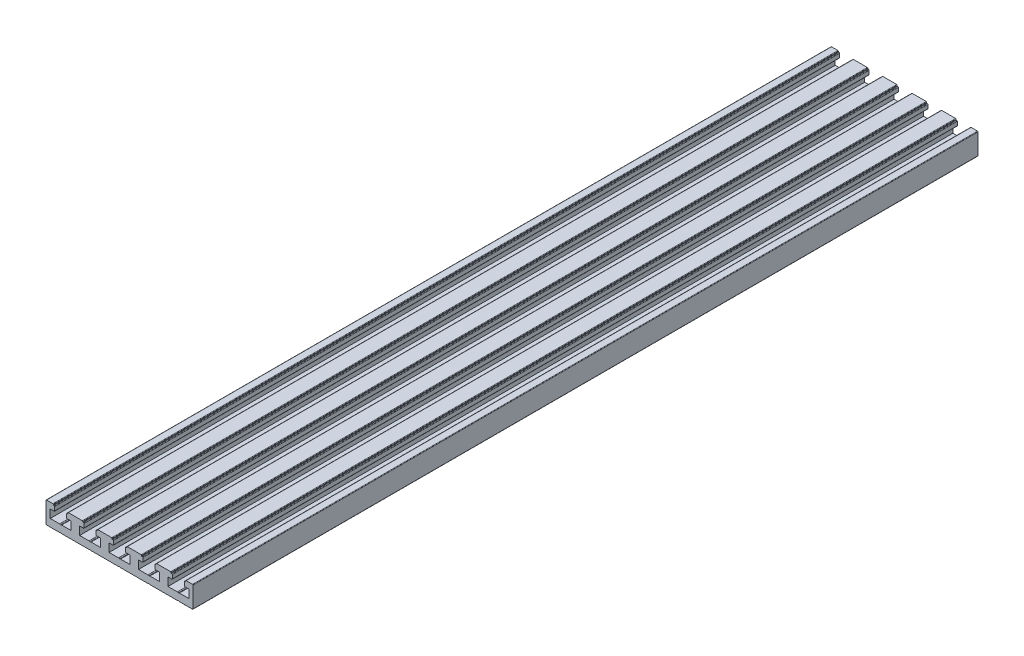
SolidWorks part; units mm, degrees
material "6061-T6 (SS)"
ref_plane "Front Plane" through (0, 0, 0) normal (0, 0, 1) x (1, 0, 0)
ref_plane "Top Plane" through (0, 0, 0) normal (0, 1, 0) x (1, 0, 0)
ref_plane "Right Plane" through (0, 0, 0) normal (1, 0, 0) x (0, 0, -1)
sketch "Sketch1" plane through (0, 0, 0) normal (0, 0, -1) x (-1, 0, 0)
  line L0 (0, 1.72) -> (0, -1.72) construction
  line L1 (-37.45, 8.85) -> (-37.45, -1.65)
  line L2 (-37.2, -1.9) -> (-30.5436, -1.9)
  line L3 (-30.4589, -1.8852) -> (-30, -1.72)
  line L4 (-30, -1.72) -> (-29.5411, -1.8852)
  line L5 (-29.4564, -1.9) -> (-15.5436, -1.9)
  line L6 (-15.4589, -1.8852) -> (-15, -1.72)
  line L7 (-15, -1.72) -> (-14.5411, -1.8852)
  line L8 (-14.4564, -1.9) -> (-0.5436, -1.9)
  line L9 (-0.4589, -1.8852) -> (0, -1.72)
  line L10 (0, -1.72) -> (0.4589, -1.8852)
  line L11 (0.5436, -1.9) -> (14.4564, -1.9)
  line L12 (14.5411, -1.8852) -> (15, -1.72)
  line L13 (15, -1.72) -> (15.4589, -1.8852)
  line L14 (15.5436, -1.9) -> (29.4564, -1.9)
  line L15 (29.5411, -1.8852) -> (30, -1.72)
  line L16 (30, -1.72) -> (30.4589, -1.8852)
  line L17 (30.5436, -1.9) -> (37.2, -1.9)
  line L18 (37.45, -1.65) -> (37.45, 8.85)
  line L19 (37.2, 9.1) -> (33.95, 9.1)
  line L20 (33.7, 8.85) -> (33.7, 8.5)
  line L21 (33.7, 8.5) -> (33.32, 8.5)
  line L22 (33.07, 8.25) -> (33.07, 6.35)
  line L23 (33.32, 6.1) -> (35.3, 6.1)
  line L24 (35.3, 6.1) -> (35.3, 1.9)
  line L25 (35.3, 1.9) -> (30.5436, 1.9)
  line L26 (30.4589, 1.8852) -> (30, 1.72)
  line L27 (30, 1.72) -> (29.5411, 1.8852)
  line L28 (29.4564, 1.9) -> (24.7, 1.9)
  line L29 (24.7, 1.9) -> (24.7, 6.1)
  line L30 (24.7, 6.1) -> (26.68, 6.1)
  line L31 (26.93, 6.35) -> (26.93, 8.25)
  line L32 (26.68, 8.5) -> (26.3, 8.5)
  line L33 (26.3, 8.5) -> (26.3, 8.85)
  line L34 (26.05, 9.1) -> (18.95, 9.1)
  line L35 (18.7, 8.85) -> (18.7, 8.5)
  line L36 (18.7, 8.5) -> (18.32, 8.5)
  line L37 (18.07, 8.25) -> (18.07, 6.35)
  line L38 (18.32, 6.1) -> (20.3, 6.1)
  line L39 (20.3, 6.1) -> (20.3, 1.9)
  line L40 (20.3, 1.9) -> (15.5436, 1.9)
  line L41 (15.4589, 1.8852) -> (15, 1.72)
  line L42 (15, 1.72) -> (14.5411, 1.8852)
  line L43 (14.4564, 1.9) -> (9.7, 1.9)
  line L44 (9.7, 1.9) -> (9.7, 6.1)
  line L45 (9.7, 6.1) -> (11.68, 6.1)
  line L46 (11.93, 6.35) -> (11.93, 8.25)
  line L47 (11.68, 8.5) -> (11.3, 8.5)
  line L48 (11.3, 8.5) -> (11.3, 8.85)
  line L49 (11.05, 9.1) -> (3.95, 9.1)
  line L50 (3.7, 8.85) -> (3.7, 8.5)
  line L51 (3.7, 8.5) -> (3.32, 8.5)
  line L52 (3.07, 8.25) -> (3.07, 6.35)
  line L53 (3.32, 6.1) -> (5.3, 6.1)
  line L54 (5.3, 6.1) -> (5.3, 1.9)
  line L55 (5.3, 1.9) -> (0.5436, 1.9)
  line L56 (0.4589, 1.8852) -> (0, 1.72)
  line L57 (0, 1.72) -> (-0.4589, 1.8852)
  line L58 (-0.5436, 1.9) -> (-5.3, 1.9)
  line L59 (-5.3, 1.9) -> (-5.3, 6.1)
  line L60 (-5.3, 6.1) -> (-3.32, 6.1)
  line L61 (-3.07, 6.35) -> (-3.07, 8.25)
  line L62 (-3.32, 8.5) -> (-3.7, 8.5)
  line L63 (-3.7, 8.5) -> (-3.7, 8.85)
  line L64 (-3.95, 9.1) -> (-11.05, 9.1)
  line L65 (-11.3, 8.85) -> (-11.3, 8.5)
  line L66 (-11.3, 8.5) -> (-11.68, 8.5)
  line L67 (-11.93, 8.25) -> (-11.93, 6.35)
  line L68 (-11.68, 6.1) -> (-9.7, 6.1)
  line L69 (-9.7, 6.1) -> (-9.7, 1.9)
  line L70 (-9.7, 1.9) -> (-14.4564, 1.9)
  line L71 (-14.5411, 1.8852) -> (-15, 1.72)
  line L72 (-15, 1.72) -> (-15.4589, 1.8852)
  line L73 (-15.5436, 1.9) -> (-20.3, 1.9)
  line L74 (-20.3, 1.9) -> (-20.3, 6.1)
  line L75 (-20.3, 6.1) -> (-18.32, 6.1)
  line L76 (-18.07, 6.35) -> (-18.07, 8.25)
  line L77 (-18.32, 8.5) -> (-18.7, 8.5)
  line L78 (-18.7, 8.5) -> (-18.7, 8.85)
  line L79 (-18.95, 9.1) -> (-26.05, 9.1)
  line L80 (-26.3, 8.85) -> (-26.3, 8.5)
  line L81 (-26.3, 8.5) -> (-26.68, 8.5)
  line L82 (-26.93, 8.25) -> (-26.93, 6.35)
  line L83 (-26.68, 6.1) -> (-24.7, 6.1)
  line L84 (-24.7, 6.1) -> (-24.7, 1.9)
  line L85 (-24.7, 1.9) -> (-29.4564, 1.9)
  line L86 (-29.5411, 1.8852) -> (-30, 1.72)
  line L87 (-30, 1.72) -> (-30.4589, 1.8852)
  line L88 (-30.5436, 1.9) -> (-35.3, 1.9)
  line L89 (-35.3, 1.9) -> (-35.3, 6.1)
  line L90 (-35.3, 6.1) -> (-33.32, 6.1)
  line L91 (-33.07, 6.35) -> (-33.07, 8.25)
  line L92 (-33.32, 8.5) -> (-33.7, 8.5)
  line L93 (-33.7, 8.5) -> (-33.7, 8.85)
  line L94 (-33.95, 9.1) -> (-37.2, 9.1)
  arc A0 (-37.45, -1.65) -> (-37.2, -1.9) centre (-37.2, -1.65) ccw
  arc A1 (-30.5436, -1.9) -> (-30.4589, -1.8852) centre (-30.5436, -1.65) ccw
  arc A2 (-29.5411, -1.8852) -> (-29.4564, -1.9) centre (-29.4564, -1.65) ccw
  arc A3 (-15.5436, -1.9) -> (-15.4589, -1.8852) centre (-15.5436, -1.65) ccw
  arc A4 (-14.5411, -1.8852) -> (-14.4564, -1.9) centre (-14.4564, -1.65) ccw
  arc A5 (-0.5436, -1.9) -> (-0.4589, -1.8852) centre (-0.5436, -1.65) ccw
  arc A6 (0.4589, -1.8852) -> (0.5436, -1.9) centre (0.5436, -1.65) ccw
  arc A7 (14.4564, -1.9) -> (14.5411, -1.8852) centre (14.4564, -1.65) ccw
  arc A8 (15.4589, -1.8852) -> (15.5436, -1.9) centre (15.5436, -1.65) ccw
  arc A9 (29.4564, -1.9) -> (29.5411, -1.8852) centre (29.4564, -1.65) ccw
  arc A10 (30.4589, -1.8852) -> (30.5436, -1.9) centre (30.5436, -1.65) ccw
  arc A11 (37.2, -1.9) -> (37.45, -1.65) centre (37.2, -1.65) ccw
  arc A12 (37.45, 8.85) -> (37.2, 9.1) centre (37.2, 8.85) ccw
  arc A13 (33.95, 9.1) -> (33.7, 8.85) centre (33.95, 8.85) ccw
  arc A14 (33.32, 8.5) -> (33.07, 8.25) centre (33.32, 8.25) ccw
  arc A15 (33.07, 6.35) -> (33.32, 6.1) centre (33.32, 6.35) ccw
  arc A16 (30.5436, 1.9) -> (30.4589, 1.8852) centre (30.5436, 1.65) ccw
  arc A17 (29.5411, 1.8852) -> (29.4564, 1.9) centre (29.4564, 1.65) ccw
  arc A18 (26.68, 6.1) -> (26.93, 6.35) centre (26.68, 6.35) ccw
  arc A19 (26.93, 8.25) -> (26.68, 8.5) centre (26.68, 8.25) ccw
  arc A20 (26.3, 8.85) -> (26.05, 9.1) centre (26.05, 8.85) ccw
  arc A21 (18.95, 9.1) -> (18.7, 8.85) centre (18.95, 8.85) ccw
  arc A22 (18.32, 8.5) -> (18.07, 8.25) centre (18.32, 8.25) ccw
  arc A23 (18.07, 6.35) -> (18.32, 6.1) centre (18.32, 6.35) ccw
  arc A24 (15.5436, 1.9) -> (15.4589, 1.8852) centre (15.5436, 1.65) ccw
  arc A25 (14.5411, 1.8852) -> (14.4564, 1.9) centre (14.4564, 1.65) ccw
  arc A26 (11.68, 6.1) -> (11.93, 6.35) centre (11.68, 6.35) ccw
  arc A27 (11.93, 8.25) -> (11.68, 8.5) centre (11.68, 8.25) ccw
  arc A28 (11.3, 8.85) -> (11.05, 9.1) centre (11.05, 8.85) ccw
  arc A29 (3.95, 9.1) -> (3.7, 8.85) centre (3.95, 8.85) ccw
  arc A30 (3.32, 8.5) -> (3.07, 8.25) centre (3.32, 8.25) ccw
  arc A31 (3.07, 6.35) -> (3.32, 6.1) centre (3.32, 6.35) ccw
  arc A32 (0.5436, 1.9) -> (0.4589, 1.8852) centre (0.5436, 1.65) ccw
  arc A33 (-0.4589, 1.8852) -> (-0.5436, 1.9) centre (-0.5436, 1.65) ccw
  arc A34 (-3.32, 6.1) -> (-3.07, 6.35) centre (-3.32, 6.35) ccw
  arc A35 (-3.07, 8.25) -> (-3.32, 8.5) centre (-3.32, 8.25) ccw
  arc A36 (-3.7, 8.85) -> (-3.95, 9.1) centre (-3.95, 8.85) ccw
  arc A37 (-11.05, 9.1) -> (-11.3, 8.85) centre (-11.05, 8.85) ccw
  arc A38 (-11.68, 8.5) -> (-11.93, 8.25) centre (-11.68, 8.25) ccw
  arc A39 (-11.93, 6.35) -> (-11.68, 6.1) centre (-11.68, 6.35) ccw
  arc A40 (-14.4564, 1.9) -> (-14.5411, 1.8852) centre (-14.4564, 1.65) ccw
  arc A41 (-15.4589, 1.8852) -> (-15.5436, 1.9) centre (-15.5436, 1.65) ccw
  arc A42 (-18.32, 6.1) -> (-18.07, 6.35) centre (-18.32, 6.35) ccw
  arc A43 (-18.07, 8.25) -> (-18.32, 8.5) centre (-18.32, 8.25) ccw
  arc A44 (-18.7, 8.85) -> (-18.95, 9.1) centre (-18.95, 8.85) ccw
  arc A45 (-26.05, 9.1) -> (-26.3, 8.85) centre (-26.05, 8.85) ccw
  arc A46 (-26.68, 8.5) -> (-26.93, 8.25) centre (-26.68, 8.25) ccw
  arc A47 (-26.93, 6.35) -> (-26.68, 6.1) centre (-26.68, 6.35) ccw
  arc A48 (-29.4564, 1.9) -> (-29.5411, 1.8852) centre (-29.4564, 1.65) ccw
  arc A49 (-30.4589, 1.8852) -> (-30.5436, 1.9) centre (-30.5436, 1.65) ccw
  arc A50 (-33.32, 6.1) -> (-33.07, 6.35) centre (-33.32, 6.35) ccw
  arc A51 (-33.07, 8.25) -> (-33.32, 8.5) centre (-33.32, 8.25) ccw
  arc A52 (-33.7, 8.85) -> (-33.95, 9.1) centre (-33.95, 8.85) ccw
  arc A53 (-37.2, 9.1) -> (-37.45, 8.85) centre (-37.2, 8.85) ccw
  point P2 (0, 0)
  dimension "D1" = 11
  dimension "D2" = 74.9
extrude "RawPart" add sketch "Sketch1" against normal blind 400
hole_wizard "CSK for M3 Flat Head Machine Screw1" positions "3DSketch1" profile "Sketch2" countersink size "M3" standard "ANSI Metric" end condition through all
sketch3d "3DSketch1"
  point P0 (-30, 1.9, 65)
  point P2 (30, 1.9, 65)
  point P35 (30, 1.9, 330)
  point P37 (-30, 1.9, 330)
  dimension "D4" = 330
  dimension "D1" = 65
  dimension "D2" = 7.45
  dimension "D3" = 60
sketch "Sketch2" plane through (-30, 1.9, 65) normal (1, 0, 0) x (0, 0, 1)
  line L0 (0, 0) -> (0, 3.8)
  line L1 (0, 3.8) -> (1.6, 3.8)
  line L2 (1.6, 3.8) -> (1.6, 1.4)
  line L3 (1.6, 1.4) -> (3, 0)
  line L5 (3, 0) -> (0, 0)
  line L6 (-1.6, 1.4) -> (-3, 0) construction
  line L11 (0, -6.35) -> (0, 107.95) construction
  dimension "Thru Hole Dia." = 3.2
  dimension "Thru Hole Depth" = 3.8
  dimension "Near C'Sink Dia." = 6
  dimension "Near C'Sink Angle" = 90
hole_wizard "M4x0.7 Tapped Hole1" positions "Sketch4" profile "Sketch5" tap size "M4x0.7" standard "ANSI Metric" end condition through all
sketch "Sketch4" plane through (0, 1.9, 0) normal (0, 1, 0) x (1, 0, 0)
  line L1 (-0.5436, 0) -> (-14.4564, 0) construction
  line L2 (-37.45, -400) -> (-37.45, 0) construction
  line L3 (15, -400) -> (15, 0) construction
  line L5 (-26.05, 0) -> (-18.95, 0) construction
  point P0 (15, -30)
  point P15 (15, -371)
  dimension "D1" = 30
  dimension "D2" = 52.45
  dimension "D3" = 371
sketch "Sketch5" plane through (15, 1.9, 30) normal (1, 0, 0) x (0, 0, 1)
  line L0 (0, 0) -> (0, 3.8)
  line L1 (0, 3.8) -> (1.65, 3.8)
  line L2 (1.65, 3.8) -> (1.65, 0)
  line L5 (1.65, 0) -> (0, 0)
  line L11 (0, -6.35) -> (0, 107.95) construction
  dimension "Thru Tap Drill Dia." = 3.3
  dimension "Thru Tap Drill Depth" = 3.8
cosmetic thread "Hole Thread4" parameters "D2"=4
cosmetic thread "Hole Thread7" parameters "D2"=4
sketch "Sketch6" [suppressed] plane through (0, 0, 0) normal (0, 0, -1) x (-1, 0, 0)
  line L1 (-14.5411, -9.9057) -> (-41.3903, -9.9057)
  line L2 (-14.5411, -9.9057) -> (-14.5411, 14.5956)
  line L3 (-14.5411, 14.5956) -> (-41.3903, 14.5956)
  line L4 (-41.3903, -9.9057) -> (-41.3903, 14.5956)
extrude "CutUnnecessaryHalf" [suppressed] cut sketch "Sketch6" against normal through all
equation "\"D4@3DSketch1\"=\"D1@RawPart\"-\"D1@3DSketch1\"-5"
